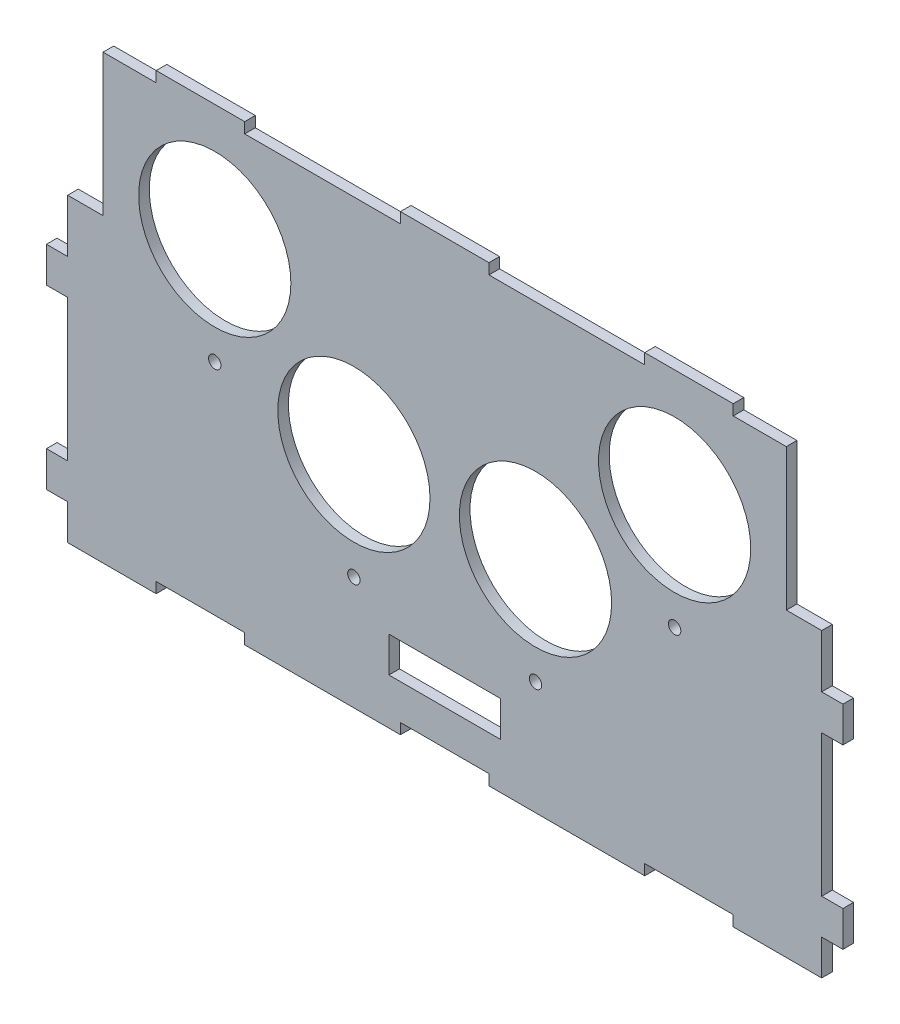
SolidWorks part; units mm, degrees
ref_plane "Спереди" through (0, 0, 0) normal (0, 0, 1) x (1, 0, 0)
ref_plane "Сверху" through (0, 0, 0) normal (0, 1, 0) x (1, 0, 0)
ref_plane "Справа" through (0, 0, 0) normal (1, 0, 0) x (0, 0, -1)
sketch "Эскиз1" plane through (0, 0, 0) normal (0, 0, 1) x (1, 0, 0)
  line L0 (95.0962, 190) -> (225, 265) construction
  line L10 (0, 20) -> (0, 40) construction
  line L12 (450, 20) -> (450, 40)
  line L13 (32, 250) -> (62, 250)
  line L15 (0, 265) -> (450, 265) construction
  line L17 (173.697, 124.0461) -> (225, 265) construction
  line L18 (225, 265) -> (276.303, 124.0461) construction
  line L19 (225, 265) -> (354.9038, 190) construction
  line L22 (0, 20) -> (0, 40) construction
  line L24 (12, 170) -> (12, 140)
  line L29 (12, 170) -> (32, 170)
  line L32 (12, 20) -> (0, 20)
  line L34 (12, 40) -> (0, 40)
  line L35 (0, 20) -> (0, 40)
  line L37 (12, 120) -> (0, 120)
  line L39 (12, 140) -> (0, 140)
  line L40 (0, 120) -> (0, 140)
  line L42 (12, 20) -> (12, 0)
  line L43 (12, 120) -> (12, 40)
  line L44 (12, 0) -> (62, 0)
  line L46 (0, 120) -> (0, 140) construction
  line L48 (0, 120) -> (0, 140) construction
  line L49 (112, 0) -> (200, 0)
  line L51 (438, 120) -> (438, 40)
  line L52 (438, 20) -> (438, 0)
  line L53 (62, 0) -> (62, 6)
  line L54 (450, 120) -> (450, 140)
  line L55 (438, 140) -> (450, 140)
  line L56 (438, 120) -> (450, 120)
  line L57 (62, 6) -> (112, 6)
  line L58 (438, 40) -> (450, 40)
  line L59 (438, 20) -> (450, 20)
  line L61 (438, 170) -> (418, 170)
  line L62 (112, 0) -> (112, 6)
  line L63 (438, 170) -> (438, 140)
  line L65 (450, 120) -> (450, 140) construction
  line L67 (418, 250) -> (418, 170)
  line L69 (200, 0) -> (200, 6)
  line L70 (200, 6) -> (250, 6)
  line L71 (250, 0) -> (250, 6)
  line L73 (338, 0) -> (338, 6)
  line L74 (338, 6) -> (388, 6)
  line L75 (388, 0) -> (388, 6)
  line L76 (250, 0) -> (338, 0)
  line L77 (388, 0) -> (438, 0)
  line L78 (112, 250) -> (200, 250)
  line L80 (200, 250) -> (200, 256)
  line L81 (200, 256) -> (250, 256)
  line L82 (250, 250) -> (250, 256)
  line L84 (32, 250) -> (32, 170)
  line L90 (338, 250) -> (338, 256)
  line L91 (338, 256) -> (388, 256)
  line L92 (388, 250) -> (388, 256)
  line L94 (112, 250) -> (112, 256)
  line L95 (112, 256) -> (62, 256)
  line L96 (62, 250) -> (62, 256)
  line L97 (250, 250) -> (338, 250)
  line L98 (388, 250) -> (418, 250)
  line L99 (193.5, 46) -> (256.5, 46)
  line L100 (193.5, 46) -> (193.5, 26)
  line L101 (193.5, 26) -> (256.5, 26)
  line L102 (256.5, 46) -> (256.5, 26)
  circle A7 centre (95.0962, 190) radius 43
  circle A8 centre (173.697, 124.0461) radius 43
  circle A9 centre (276.303, 124.0461) radius 43
  circle A10 centre (354.9038, 190) radius 43
  circle A11 centre (95.0962, 130) radius 3.5
  circle A12 centre (173.697, 64.0461) radius 3.5
  circle A13 centre (276.303, 64.0461) radius 3.5
  circle A14 centre (354.9038, 130) radius 3.5
  point P17 (225, 265)
  point P47 (225, 26)
  point P52 (225, 250)
  point P54 (225, 6)
  point P75 (0, 0)
  point P76 (0, 0)
  point P77 (0, 0)
  point P78 (0, 0)
  point P79 (0, 0)
  point P80 (0, 0)
  dimension "D4" = 30
  dimension "D5" = 86
  dimension "D6" = 150
  dimension "D7" = 4
  dimension "D8" = 40
  dimension "D9" = 40
  dimension "D12" = 30
  dimension "D53" = 7
  dimension "D54" = 7
  dimension "D55" = 7
  dimension "D56" = 7
  dimension "D3" = 15
  dimension "D10" = 40
  dimension "D11" = 80
  dimension "D13" = 12
  dimension "D14" = 20
  dimension "D15" = 20
  dimension "D16" = 80
  dimension "D17" = 265
  dimension "D18" = 30
  dimension "D19" = 30
  dimension "D20" = 193
  dimension "D21" = 20
  dimension "D22" = 20
  dimension "D23" = 20
  dimension "D24" = 20
  dimension "D25" = 30
  dimension "D26" = 20
  dimension "D27" = 20
  dimension "D28" = 80
  dimension "D29" = 426
  dimension "D30" = 12
  dimension "D31" = 12
  dimension "D32" = 426
  dimension "D33" = 50
  dimension "D34" = 50
  dimension "D35" = 50
  dimension "D36" = 6
  dimension "D37" = 50
  dimension "D38" = 50
  dimension "D39" = 6
  dimension "D40" = 6
  dimension "D41" = 88
  dimension "D42" = 6
  dimension "D43" = 80
  dimension "D44" = 50
  dimension "D45" = 50
  dimension "D46" = 88
  dimension "D47" = 88
  dimension "D48" = 6
  dimension "D49" = 6
  dimension "D50" = 20
  dimension "D51" = 63
  dimension "D52" = 20
  dimension "D57" = 60
  dimension "D58" = 60
  dimension "D59" = 60
  dimension "D60" = 60
extrude "Бобышка-Вытянуть2" add sketch "Эскиз1" along normal blind 6
